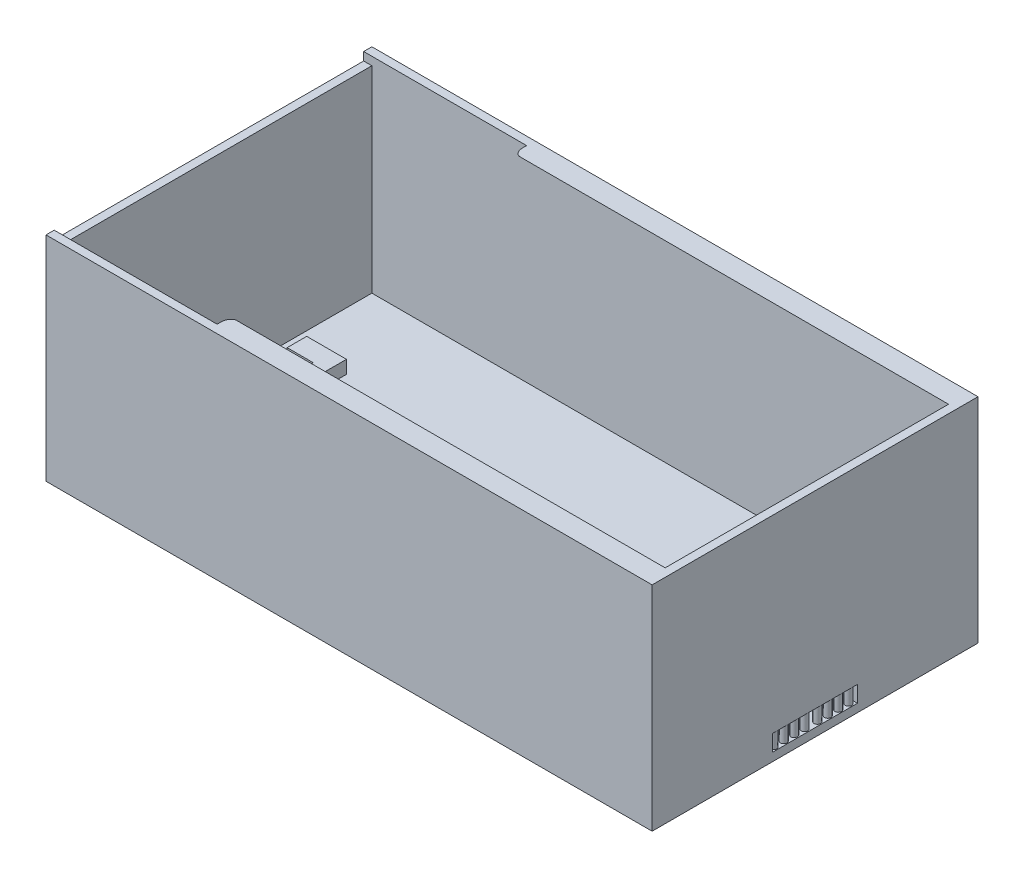
SolidWorks part; units mm, degrees
ref_plane "Plano frontal" through (0, 0, 0) normal (0, 0, 1) x (1, 0, 0)
ref_plane "Plano superior" through (0, 0, 0) normal (0, 1, 0) x (1, 0, 0)
ref_plane "Plano direito" through (0, 0, 0) normal (1, 0, 0) x (0, 0, -1)
sketch "Esboço1" plane through (0, 0, 0) normal (0, 1, 0) x (1, 0, 0)
  line L1 (0, 0) -> (93, 0)
  line L2 (0, 0) -> (0, -50)
  line L3 (0, -50) -> (93, -50)
  line L4 (93, 0) -> (93, -50)
  dimension "D1" = 93
  dimension "D2" = 50
extrude "Ressalto-extrusão1" add sketch "Esboço1" along normal blind 1.26
sketch "Esboço2" plane through (0, 0, 0) normal (0, 1, 0) x (1, 0, 0)
  line L0 (93, -50) -> (93, 0) construction
  line L1 (0, 0) -> (93, 0)
  line L2 (0, 0) -> (0, -1.26)
  line L3 (0, -1.26) -> (93, -1.26)
  line L4 (93, 0) -> (93, -1.26)
  line L6 (0, -50) -> (93, -50)
  line L7 (0, -50) -> (0, -48.74)
  line L8 (0, -48.74) -> (93, -48.74)
  line L9 (93, -50) -> (93, -48.74)
  dimension "D1" = 1.26
  dimension "D2" = 1.26
extrude "Ressalto-extrusão2" add sketch "Esboço2" along normal blind 32.74
sketch "Esboço3" plane through (0, 0, 0) normal (0, 1, 0) x (1, 0, 0)
  line L0 (0, -50) -> (93, -50) construction
  line L1 (93, 0) -> (91.74, 0)
  line L2 (93, 0) -> (93, -50)
  line L3 (93, -50) -> (91.74, -50)
  line L4 (91.74, 0) -> (91.74, -50)
  dimension "D1" = 1.26
extrude "Ressalto-extrusão4" add sketch "Esboço3" along normal blind 32.74
sketch "Esboço5" plane through (0, 0, 0) normal (1, 0, 0) x (0, 0, -1)
  line L0 (0, 32.74) -> (-3.26, 32.74)
  line L1 (-1.26, 32.74) -> (-48.74, 32.74) construction
  line L2 (-3.26, 32.74) -> (0, 29.48)
  line L4 (-50, 32.74) -> (-46.74, 32.74)
  line L5 (-46.74, 32.74) -> (-50, 29.48)
  line L6 (-50, 32.74) -> (-50, 0) construction
  line L7 (-50, 29.48) -> (-50, 32.74)
  line L8 (0, 32.74) -> (0, 0) construction
  line L9 (0, 29.48) -> (0, 32.74)
  dimension "D1" = 3.26
  dimension "D2" = 3.26
extrude "Ressalto-extrusão5" add sketch "Esboço5" along normal blind 67 from offset 25
fillet "Filete1" radius 1 1 edges at (25, 31.74, 47.74)
fillet "Filete2" radius 1 1 edges at (25, 31.74, 2.26)
sketch "Esboço6" plane through (0, 0, 0) normal (0, 1, 0) x (1, 0, 0)
  line L0 (0, -50) -> (93, -50) construction
  line L1 (0, 0) -> (1.26, 0)
  line L2 (0, 0) -> (0, -50)
  line L3 (0, -50) -> (1.26, -50)
  line L4 (1.26, 0) -> (1.26, -50)
  dimension "D1" = 1.26
extrude "Ressalto-extrusão6" add sketch "Esboço6" along normal blind 31.48
sketch "Esboço7" plane through (0, 0, 0) normal (-1, 0, 0) x (0, 0, 1)
  line L0 (0, 0) -> (50, 0) construction
  line L1 (19.5, 3.76) -> (30.5, 3.76)
  line L2 (19.5, 3.76) -> (19.5, 1.26)
  line L3 (19.5, 1.26) -> (30.5, 1.26)
  line L4 (30.5, 3.76) -> (30.5, 1.26)
  line L5 (0, 32.74) -> (0, 0) construction
  dimension "D1" = 1.26
  dimension "D2" = 2.5
  dimension "D3" = 19.5
  dimension "D4" = 11
extrude "Corte-extrusão1" cut sketch "Esboço7" against normal blind 1.26
sketch "Esboço8" plane through (93, 0, 0) normal (1, 0, 0) x (0, 0, -1)
  line L0 (-50, 0) -> (0, 0) construction
  line L1 (-31.5, 3.76) -> (-18.5, 3.76)
  line L2 (-31.5, 3.76) -> (-31.5, 1.26)
  line L3 (-31.5, 1.26) -> (-18.5, 1.26)
  line L4 (-18.5, 3.76) -> (-18.5, 1.26)
  line L5 (-50, 32.74) -> (-50, 0) construction
  dimension "D1" = 13
  dimension "D2" = 2.5
  dimension "D3" = 1.26
  dimension "D4" = 18.5
extrude "Corte-extrusão2" cut sketch "Esboço8" against normal blind 1.26
sketch "Esboço10" plane through (0, 1.26, 0) normal (0, 1, 0) x (1, 0, 0)
  line L0 (4, -14) -> (4, -17)
  line L1 (4, -17) -> (8, -17)
  line L2 (8, -17) -> (8, -19)
  line L3 (8, -19) -> (10.1, -19)
  line L4 (10.1, -19) -> (10.1, -14)
  line L5 (10.1, -14) -> (4, -14)
  line L6 (4, -33) -> (4, -36)
  line L7 (4, -36) -> (10.1, -36)
  line L8 (10.1, -36) -> (10.1, -31)
  line L9 (10.1, -31) -> (8, -31)
  line L10 (8, -31) -> (8, -33)
  line L11 (8, -33) -> (4, -33)
  line L12 (1.26, -48.74) -> (91.74, -48.74) construction
  line L13 (0, -1.26) -> (0, -48.74) construction
  dimension "D1" = 2.1
  dimension "D2" = 2.1
  dimension "D3" = 3
  dimension "D4" = 3
  dimension "D5" = 8
  dimension "D6" = 8
  dimension "D7" = 16
  dimension "D8" = 2
  dimension "D9" = 2
  dimension "D10" = 2.5
  dimension "D11" = 4
extrude "Ressalto-extrusão7" add sketch "Esboço10" along normal blind 2
sketch "Esboço11" plane through (0, 1.26, 0) normal (0, 1, 0) x (1, 0, 0)
  line L0 (87.74, -12.74) -> (82.9, -12.74)
  line L1 (82.9, -12.74) -> (82.9, -18)
  line L2 (82.9, -18) -> (85, -18)
  line L3 (85, -18) -> (85, -16)
  line L4 (85, -16) -> (87.74, -16)
  line L5 (87.74, -16) -> (87.74, -12.74)
  line L6 (87.74, -34) -> (87.74, -37.26)
  line L7 (87.74, -37.26) -> (82.9, -37.26)
  line L8 (82.9, -37.26) -> (82.9, -32)
  line L9 (82.9, -32) -> (85, -32)
  line L10 (85, -32) -> (85, -34)
  line L11 (85, -34) -> (87.74, -34)
  line L12 (91.74, -48.74) -> (91.74, -31.5) construction
  line L13 (93, -50) -> (93, 0) construction
  line L14 (0, -50) -> (93, -50) construction
  dimension "D1" = 3.26
  dimension "D2" = 2.1
  dimension "D3" = 4
  dimension "D4" = 8
  dimension "D5" = 18
  dimension "D6" = 16
  dimension "D7" = 2
extrude "Ressalto-extrusão8" add sketch "Esboço11" along normal blind 2
sketch "Esboço13" plane through (0, 0, 0) normal (0, -1, 0) x (1, 0, 0)
  line L0 (93, 25) -> (75.5822, 25) construction
  line L1 (93, 50) -> (93, 0) construction
  line L2 (46.5, 50) -> (46.5, -4.1144) construction
  line L3 (0, 50) -> (93, 50) construction
  circle A0 centre (92.37, 30.775) radius 0.5
  circle A1 centre (92.37, 29.175) radius 0.5
  circle A2 centre (92.37, 27.575) radius 0.5
  circle A3 centre (92.37, 25.975) radius 0.5
  circle A4 centre (92.37, 24.025) radius 0.5
  circle A5 centre (92.37, 22.425) radius 0.5
  circle A6 centre (92.37, 20.825) radius 0.5
  circle A7 centre (92.37, 19.225) radius 0.5
  circle A8 centre (0.63, 19.225) radius 0.5
  circle A9 centre (0.63, 20.825) radius 0.5
  circle A10 centre (0.63, 22.425) radius 0.5
  circle A11 centre (0.63, 24.025) radius 0.5
  circle A12 centre (0.63, 25.975) radius 0.5
  circle A13 centre (0.63, 27.575) radius 0.5
  circle A14 centre (0.63, 29.175) radius 0.5
  circle A15 centre (0.63, 30.775) radius 0.5
  dimension "D1" = 1
  dimension "D2" = 1.6
  dimension "D3" = 1.6
  dimension "D4" = 1.6
  dimension "D5" = 0.725
  dimension "D6" = 0.63
extrude "Ressalto-extrusão9" add sketch "Esboço13" against normal blind 4
